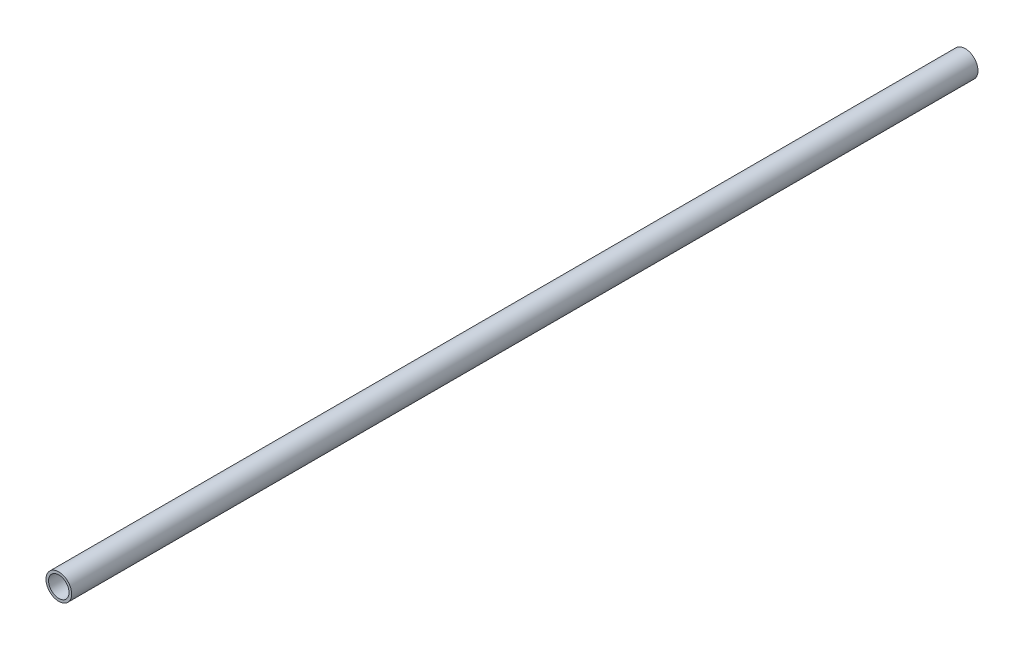
SolidWorks part; units mm, degrees
ref_plane "Front Plane" through (0, 0, 0) normal (0, 0, 1) x (1, 0, 0)
ref_plane "Top Plane" through (0, 0, 0) normal (0, 1, 0) x (1, 0, 0)
ref_plane "Right Plane" through (0, 0, 0) normal (1, 0, 0) x (0, 0, -1)
sketch "Sketch1" plane through (0, 0, 0) normal (0, 0, 1) x (1, 0, 0)
  circle A0 centre (0, 0) radius 16.7005
  circle A1 centre (0, 0) radius 13.3223
  dimension "D1" = 33.401
  dimension "D2" = 26.8462
  dimension " 0.493" = 26.6446
extrude "Boss-Extrude1" add sketch "Sketch1" along normal blind 1181.1
